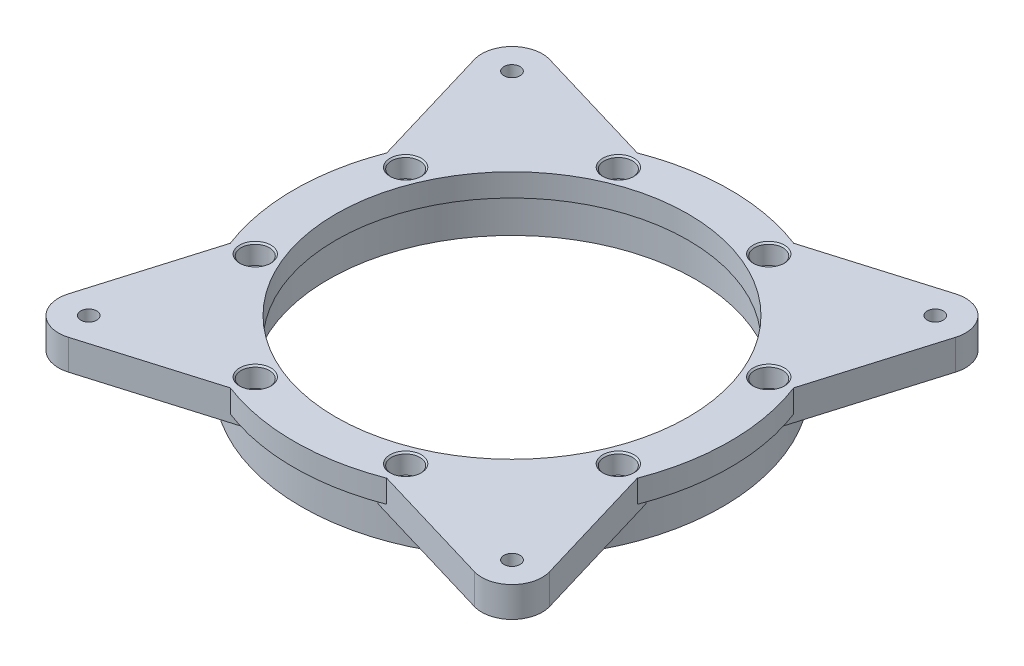
SolidWorks part; units mm, degrees
ref_plane "Front Plane" through (0, 0, 0) normal (0, 0, 1) x (1, 0, 0)
ref_plane "Top Plane" through (0, 0, 0) normal (0, 1, 0) x (1, 0, 0)
ref_plane "Right Plane" through (0, 0, 0) normal (1, 0, 0) x (0, 0, -1)
sketch "Sketch1" plane through (0, 0, 0) normal (0, 1, 0) x (1, 0, 0)
  circle A0 centre (112.8644, 65.4004) radius 88.395
  circle A2 centre (112.8644, 65.4004) radius 76.1365
  circle A3 centre (81.2739, 141.6667) radius 3.556
  circle A4 centre (144.4549, 141.6667) radius 3.556
  circle A5 centre (36.5981, 96.991) radius 3.556
  circle A6 centre (36.5981, 33.8099) radius 3.556
  circle A7 centre (81.2739, -10.8658) radius 3.556
  circle A8 centre (144.4549, -10.8658) radius 3.7114
  circle A9 centre (189.1306, 33.8099) radius 3.556
  circle A10 centre (189.1306, 96.991) radius 3.556
sketch "Sketch2" plane through (0, 0, 0) normal (0, 1, 0) x (1, 0, 0)
  circle A0 centre (112.8644, 65.4004) radius 88.395
  circle A4 centre (112.8644, 65.4004) radius 77.1365
  circle A5 centre (112.8644, 65.4004) radius 77.1365
  dimension "D2" = 176.79
  dimension "D1" = 1
extrude "Boss-Extrude1" add sketch "Sketch2" along normal blind 25.4
sketch "Sketch7" plane through (0, 25.4, 0) normal (0, 1, 0) x (1, 0, 0)
  line L0 (5.1013, 173.1635) -> (112.8644, 65.4004) construction
  line L1 (27.5864, 166.473) -> (85.16, 149.3418)
  line L2 (11.7918, 150.6785) -> (28.9231, 93.1048)
  line L3 (198.1424, 166.473) -> (140.5688, 149.3418)
  line L4 (213.9369, 150.6785) -> (196.8057, 93.1048)
  line L5 (213.9369, -19.8776) -> (196.8057, 37.696)
  line L6 (198.1424, -35.6721) -> (140.5688, -18.5409)
  line L7 (27.5864, -35.6721) -> (85.16, -18.5409)
  line L8 (11.7918, -19.8776) -> (28.9231, 37.696)
  arc A0 (85.16, 149.3418) -> (28.9231, 93.1048) centre (112.8644, 65.4004) ccw
  arc A1 (27.5864, 166.473) -> (11.7918, 150.6785) centre (23.9644, 154.3004) ccw
  circle A2 centre (112.8644, 65.4004) radius 88.395 construction
  arc A3 (196.8057, 93.1048) -> (140.5688, 149.3418) centre (112.8644, 65.4004) ccw
  arc A4 (213.9369, 150.6785) -> (198.1424, 166.473) centre (201.7644, 154.3004) ccw
  arc A5 (140.5688, -18.5409) -> (196.8057, 37.696) centre (112.8644, 65.4004) ccw
  arc A6 (198.1424, -35.6721) -> (213.9369, -19.8776) centre (201.7644, -23.4996) ccw
  arc A7 (28.9231, 37.696) -> (85.16, -18.5409) centre (112.8644, 65.4004) ccw
  arc A8 (11.7918, -19.8776) -> (27.5864, -35.6721) centre (23.9644, -23.4996) ccw
  point P28 (112.8644, 65.4004)
  dimension "D3" = 25.4
  dimension "D5" = 4
  dimension "D1" = 88.9
  dimension "D2" = 88.9
  dimension "D4" = 152.4
extrude "Boss-Extrude2" add sketch "Sketch7" against normal blind 12.7
sketch "Sketch8" plane through (0, 12.7, 0) normal (0, -1, 0) x (1, 0, 0)
  circle A0 centre (23.9644, 23.4996) radius 7.1842
  circle A1 centre (201.7644, 23.4996) radius 7.1842
  circle A2 centre (201.7644, -154.3004) radius 7.1842
  circle A3 centre (23.9644, -154.3004) radius 7.1842
  point P0 (23.9644, 23.4996)
  point P5 (201.7644, 23.4996)
  point P7 (201.7644, -154.3004)
  point P9 (23.9644, -154.3004)
  dimension "D1" = 2
  dimension "D2" = 2
hole_wizard "CBORE for 1/4 Socket Head Cap Screw1" positions "Sketch8" profile "Sketch9" counterbore size "1/4" standard "ANSI Inch" end condition through all
sketch "Sketch9" plane through (23.9644, 12.7, 23.4996) normal (1, 0, 0) x (0, 0, -1)
  line L0 (0, 0) -> (0, 12.7)
  line L1 (0, 12.7) -> (3.3782, 12.7)
  line L3 (3.3782, 12.7) -> (3.3782, 6.35)
  line L4 (5.5562, 6.35) -> (3.3782, 6.35)
  line L5 (5.5562, 6.35) -> (5.5562, 0.635)
  line L6 (5.5562, 0.635) -> (6.1913, 0)
  line L7 (6.1913, 0) -> (0, 0)
  line L8 (-5.5562, 0.635) -> (-6.1913, 0) construction
  line L11 (0, -6.35) -> (0, 107.95) construction
  dimension "Thru Hole Dia." = 6.7564
  dimension "Thru Hole Depth" = 12.7
  dimension "C'Bore Dia." = 11.1125
  dimension "C'Bore Depth" = 6.35
  dimension "Near C'Sink Dia." = 12.3825
  dimension "Near C'Sink Angle" = 90
sketch "Sketch10" plane through (0, 25.4, 0) normal (0, 1, 0) x (1, 0, 0)
  circle A2 centre (112.8644, 65.4004) radius 73.9615
  circle A3 centre (112.8644, 65.4004) radius 73.9615
  circle A6 centre (112.8644, 65.4004) radius 91.57
  circle A7 centre (112.8644, 65.4004) radius 91.57
  dimension "D1" = 3.175
  dimension "D2" = 3.175
extrude "Boss-Extrude3" add sketch "Sketch10" against normal blind 9.525
sketch "Sketch5" plane through (0, 25.4, 0) normal (0, 1, 0) x (1, 0, 0)
  circle A12 centre (36.5981, 96.991) radius 5.056
  circle A13 centre (36.5981, 96.991) radius 5.056
  circle A15 centre (81.2739, 141.6667) radius 5.056
  circle A16 centre (81.2739, 141.6667) radius 5.056
  circle A18 centre (144.4549, 141.6667) radius 5.056
  circle A19 centre (144.4549, 141.6667) radius 5.056
  circle A21 centre (189.1306, 96.991) radius 5.056
  circle A22 centre (189.1306, 96.991) radius 5.056
  circle A24 centre (36.5981, 33.8099) radius 5.056
  circle A25 centre (36.5981, 33.8099) radius 5.056
  circle A27 centre (81.2739, -10.8658) radius 5.056
  circle A28 centre (81.2739, -10.8658) radius 5.056
  circle A30 centre (144.4549, -10.8658) radius 5.2114
  circle A31 centre (144.4549, -10.8658) radius 5.2114
  circle A33 centre (189.1306, 33.8099) radius 5.056
  circle A34 centre (189.1306, 33.8099) radius 5.056
  dimension "D1" = 1.5
  dimension "D2" = 1.5
  dimension "D3" = 1.5
  dimension "D4" = 1.5
  dimension "D5" = 1.5
  dimension "D6" = 1.5
  dimension "D7" = 1.5
  dimension "D8" = 1.5
sketch "Sketch11" plane through (0, 25.4, 0) normal (0, 1, 0) x (1, 0, 0)
  point P0 (36.5981, 33.8099)
  point P3 (36.5981, 96.991)
  point P6 (81.2739, 141.6667)
  point P9 (144.4549, 141.6667)
  point P12 (189.1306, 96.991)
  point P15 (189.1306, 33.8099)
  point P18 (144.4549, -10.8658)
  point P21 (81.2739, -10.8658)
hole_wizard "CBORE for 1/4 Button Head Cap Screw1" positions "Sketch11" profile "Sketch12" counterbore size "1/4" standard "ANSI Inch" end condition through all
sketch "Sketch12" plane through (36.5981, 25.4, -33.8099) normal (1, 0, 0) x (0, 0, 1)
  line L0 (0, 0) -> (0, 25.4)
  line L1 (0, 25.4) -> (3.3782, 25.4)
  line L3 (3.3782, 25.4) -> (3.3782, 8.3528)
  line L4 (5.9538, 8.3528) -> (3.3782, 8.3528)
  line L5 (5.9538, 8.3528) -> (5.9538, 0.635)
  line L6 (5.9538, 0.635) -> (6.5888, 0)
  line L7 (6.5888, 0) -> (0, 0)
  line L8 (-5.9538, 0.635) -> (-6.5888, 0) construction
  line L11 (0, -6.35) -> (0, 107.95) construction
  dimension "Thru Hole Dia." = 6.7564
  dimension "Thru Hole Depth" = 25.4
  dimension "C'Bore Dia." = 11.9075
  dimension "C'Bore Depth" = 8.3528
  dimension "Near C'Sink Dia." = 13.1775
  dimension "Near C'Sink Angle" = 90
